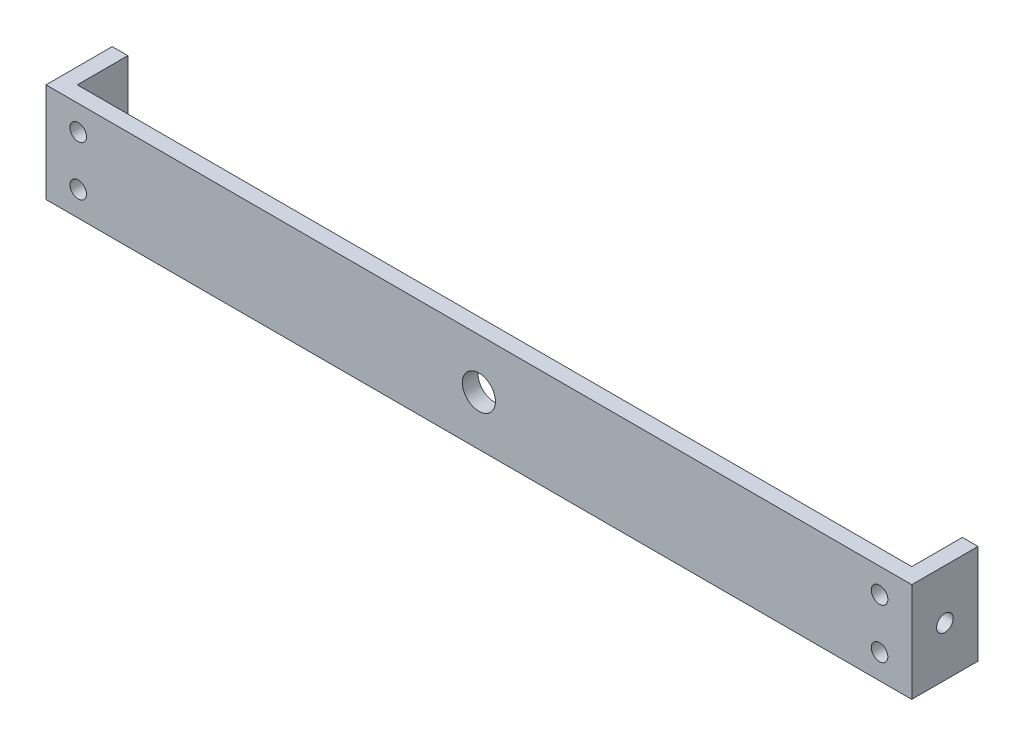
SolidWorks part; units mm, degrees
ref_plane "Alzado" through (0, 0, 0) normal (0, 0, 1) x (1, 0, 0)
ref_plane "Planta" through (0, 0, 0) normal (0, 1, 0) x (1, 0, 0)
ref_plane "Vista lateral" through (0, 0, 0) normal (1, 0, 0) x (0, 0, -1)
sketch "Croquis1" plane through (0, 0, 0) normal (0, 0, 1) x (1, 0, 0)
  line L1 (160, -19.05) -> (-160, -19.05)
  line L2 (160, -19.05) -> (160, 19.05)
  line L3 (160, 19.05) -> (-160, 19.05)
  line L4 (-160, -19.05) -> (-160, 19.05)
  line L5 (160, -19.05) -> (-160, 19.05) construction
  line L6 (160, 19.05) -> (-160, -19.05) construction
  circle A0 centre (0, 0) radius 6.35
  point P0 (0, 0)
  dimension "D3" = 12.7
  dimension "D1" = 320
  dimension "D2" = 38.1
extrude "Saliente-Extruir1" add sketch "Croquis1" along normal blind 6
sketch "Croquis3" plane through (0, 0, 6) normal (0, 0, 1) x (1, 0, 0)
  line L1 (160, 19.05) -> (166, 19.05)
  line L2 (160, 19.05) -> (160, -19.05)
  line L3 (160, -19.05) -> (166, -19.05)
  line L4 (166, 19.05) -> (166, -19.05)
  line L5 (-160, 19.05) -> (-166, 19.05)
  line L6 (-160, 19.05) -> (-160, -19.05)
  line L7 (-160, -19.05) -> (-166, -19.05)
  line L8 (-166, 19.05) -> (-166, -19.05)
  dimension "D1" = 6
  dimension "D2" = 6
extrude "Saliente-Extruir2" add sketch "Croquis3" against normal blind 25.4
sketch "Croquis4" plane through (0, 0, 0) normal (0, 0, -1) x (-1, 0, 0)
  line L0 (0, -19.05) -> (0, 19.05) construction
  line L1 (-160, 19.05) -> (160, 19.05) construction
  line L2 (160, -19.05) -> (-160, -19.05) construction
  line L3 (153.65, 0) -> (153.65, 19.05) construction
  line L4 (153.65, 0) -> (153.65, -19.05) construction
  line L5 (160, 19.05) -> (160, -19.05) construction
  circle A0 centre (153.65, 9.525) radius 3.175
  circle A1 centre (153.65, -9.525) radius 3.175
  circle A2 centre (-153.65, -9.525) radius 3.175
  circle A3 centre (-153.65, 9.525) radius 3.175
  dimension "D2" = 6.35
  dimension "D3" = 6.35
  dimension "D1" = 6.35
extrude "Cortar-Extruir1" cut sketch "Croquis4" against normal blind 25.4
sketch "Croquis5" plane through (166, 0, 0) normal (1, 0, 0) x (0, 0, -1)
  line L0 (-6, 0) -> (19.4, 0) construction
  line L1 (-6, -19.05) -> (-6, 19.05) construction
  line L2 (19.4, -19.05) -> (19.4, 19.05) construction
  circle A0 centre (6.7, 0) radius 3.175
  dimension "D1" = 6.35
extrude "Cortar-Extruir2" cut sketch "Croquis5" against normal blind 348.713
